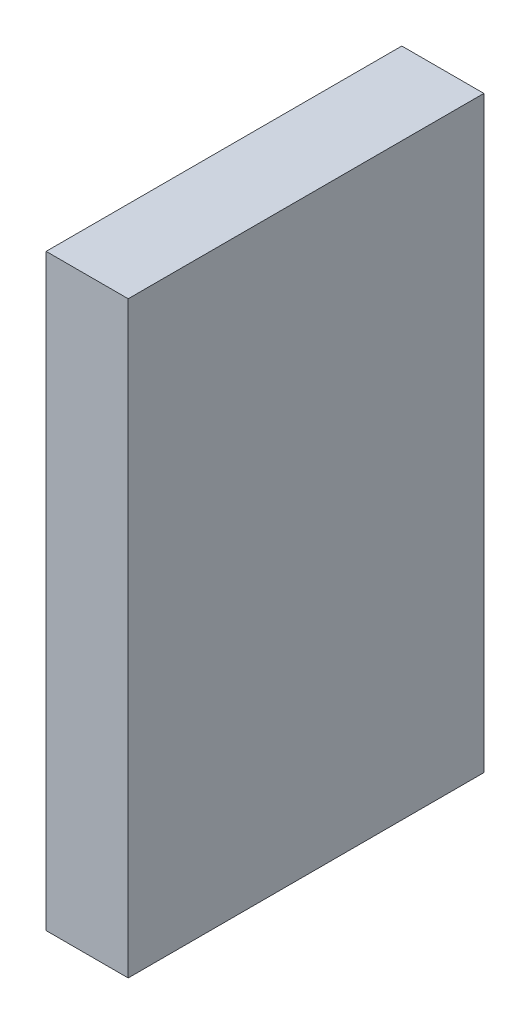
SolidWorks part; units mm, degrees
material "Espuma flexível de poliuretano"
ref_plane "Plano frontal" through (0, 0, 0) normal (0, 0, 1) x (1, 0, 0)
ref_plane "Plano superior" through (0, 0, 0) normal (0, 1, 0) x (1, 0, 0)
ref_plane "Plano direito" through (0, 0, 0) normal (1, 0, 0) x (0, 0, -1)
sketch "Esboço1" plane through (0, 0, 0) normal (0, 1, 0) x (1, 0, 0)
  line L1 (0, 0) -> (3, 0)
  line L2 (0, 0) -> (0, 13)
  line L3 (0, 13) -> (3, 13)
  line L4 (3, 0) -> (3, 13)
  dimension "D1" = 3
  dimension "D2" = 13
extrude "Ressalto-extrusão1" add sketch "Esboço1" along normal blind 21.5
